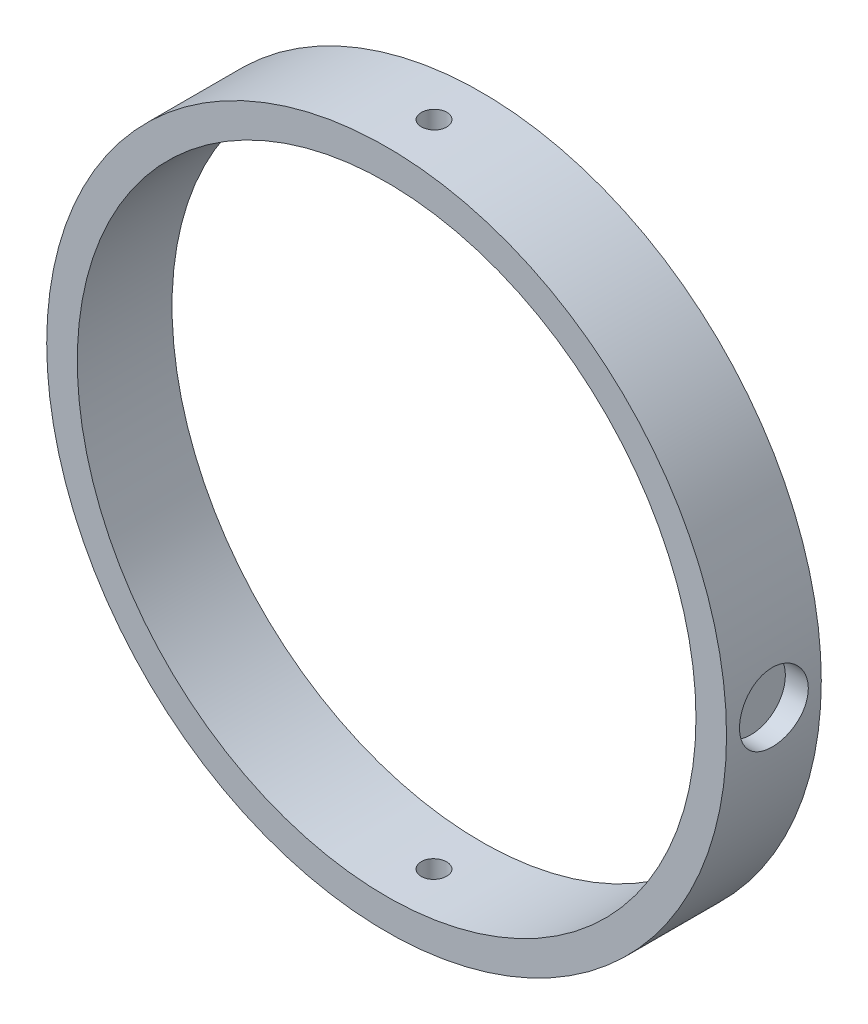
SolidWorks part; units mm, degrees
ref_plane "Plano frontal" through (0, 0, 0) normal (0, 0, 1) x (1, 0, 0)
ref_plane "Plano superior" through (0, 0, 0) normal (0, 1, 0) x (1, 0, 0)
ref_plane "Plano direito" through (0, 0, 0) normal (1, 0, 0) x (0, 0, -1)
sketch "Esboço2" plane through (0, 0, 0) normal (0, 0, 1) x (1, 0, 0)
  circle A0 centre (0, 0) radius 111.2
  circle A1 centre (0, 0) radius 101.2
  dimension "D1" = 222.4
  dimension "D2" = 202.4
extrude "Ressalto-extrusão1" add sketch "Esboço2" along normal blind 31
ref_plane "Plano1" through (111.2, 0, 0) normal (1, 0, 0) x (0, 0, -1)
ref_plane "Plano2" through (0, 111.2, 0) normal (0, 1, 0) x (1, 0, 0)
sketch "Esboço5" plane through (0, 111.2, 0) normal (0, 1, 0) x (1, 0, 0)
  line L0 (0, -17.05) -> (0, 17.05) construction
  point P0 (0, -15.5)
  dimension "D1" = 15.5
hole_wizard "Furo roscado para conduíte de M8x1.251" positions "3DSketch2" profile "Esboço7" tap size "M8x1.25" standard "Helicoil® Metric"
sketch3d "3DSketch2"
  point P0 (0, 111.2, 15.5)
  point P2 (0, 111.2, 15.5)
  point P5 (0, 111.2, 15.5)
sketch "Esboço7" plane through (0, 111.2, 15.5) normal (1, 0, 0) x (0, 0, 1)
  line L0 (0, 0) -> (0, 10)
  line L1 (0, 10) -> (4.15, 10)
  line L2 (4.15, 10) -> (4.15, 0)
  line L5 (4.15, 0) -> (0, 0)
  line L11 (0, -6.35) -> (0, 107.95) construction
  dimension "Thru Tap Drill Dia." = 8.3
  dimension "Thru Tap Drill Depth" = 10
cosmetic thread "Rosca de furo1" parameters "D1"=0, "D2"=9.3
ref_plane "Plano3" through (0, -111.2, 0) normal (0, 1, 0) x (1, 0, 0)
sketch "Esboço8" plane through (0, -111.2, 0) normal (0, 1, 0) x (1, 0, 0)
  point P0 (0, -15.5)
hole_wizard "Furo roscado para conduíte de M8x1.252" positions "3DSketch3" profile "Esboço9" tap size "M8x1.25" standard "Helicoil® Metric" end condition up to next
sketch3d "3DSketch3"
  point P0 (0, -111.2, 15.5)
  point P3 (0, -111.2, 15.5)
sketch "Esboço9" plane through (0, -111.2, 15.5) normal (1, 0, 0) x (0, 0, -1)
  line L0 (0, 0) -> (0, 212.401)
  line L1 (0, 212.401) -> (4.15, 212.401)
  line L2 (4.15, 212.401) -> (4.15, 0)
  line L5 (4.15, 0) -> (0, 0)
  line L11 (0, -6.35) -> (0, 107.95) construction
  dimension "Thru Tap Drill Dia." = 8.3
  dimension "Thru Tap Drill Depth" = 212.401
cosmetic thread "Rosca de furo2" parameters "D1"=0, "D2"=9.3
sketch "Esboço12" plane through (111.2, 0, 0) normal (1, 0, 0) x (0, 0, -1)
  line L0 (17.05, 0) -> (-17.05, 0) construction
  circle A0 centre (-15.5, 0) radius 11.25
  dimension "D1" = 22.5
  dimension "D2" = 15.5
extrude "Corte-extrusão1" cut sketch "Esboço12" against normal blind 7.5
mirror "Espelhar1" about plane through (0, 0, 0) normal (1, 0, 0) of "Corte-extrusão1"
